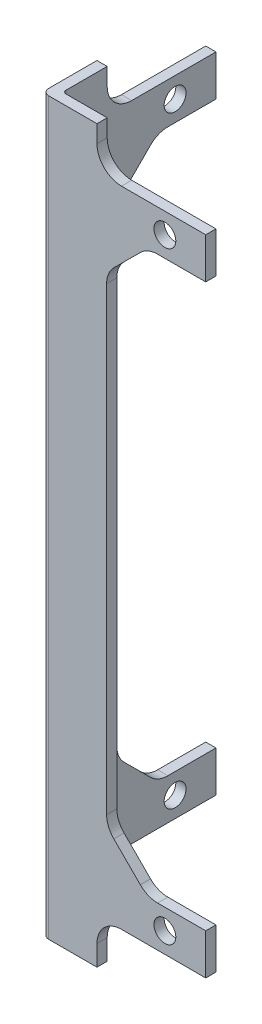
SolidWorks part; units mm, degrees
material "6061-T6 (SS)"
ref_plane "Front Plane" through (0, 0, 0) normal (0, 0, 1) x (1, 0, 0)
ref_plane "Top Plane" through (0, 0, 0) normal (0, 1, 0) x (1, 0, 0)
ref_plane "Right Plane" through (0, 0, 0) normal (1, 0, 0) x (0, 0, -1)
sketch "Sketch1" plane through (0, 0, 0) normal (0, 1, 0) x (1, 0, 0)
  line L1 (-12.7, -12.7) -> (12.7, -12.7)
  line L2 (-12.7, -12.7) -> (-12.7, 12.7)
  line L3 (-12.7, 12.7) -> (12.7, 12.7)
  line L4 (12.7, -12.7) -> (12.7, 12.7)
  line L5 (-12.7, -12.7) -> (12.7, 12.7) construction
  line L6 (-12.7, 12.7) -> (12.7, -12.7) construction
  point P0 (0, 0)
  dimension "D1" = 25.4
  dimension "D2" = 25.4
extrude "Boss-Extrude1" add sketch "Sketch1" along normal mid plane 113.5
sketch "Sketch2" plane through (0, 56.75, 0) normal (0, 1, 0) x (1, 0, 0)
  line L0 (-12.7, 12.7) -> (-12.7, -12.7) construction
  line L1 (12.7, 12.7) -> (-11.1125, 12.7)
  line L2 (12.7, 12.7) -> (12.7, -11.1125)
  line L3 (12.7, -11.1125) -> (-11.1125, -11.1125)
  line L4 (-11.1125, 12.7) -> (-11.1125, -11.1125)
  line L5 (-12.7, -12.7) -> (12.7, -12.7) construction
  dimension "D1" = 1.5875
  dimension "D2" = 1.5875
extrude "Cut-Extrude1" cut sketch "Sketch2" against normal through all
fillet "Fillet1" radius 0.508 1 edges at (-11.1125, 0, 11.1125)
hole_wizard "M3 Clearance Hole1" positions "Sketch3" profile "Sketch4" hole size "M3" standard "ANSI Metric" end condition through all
sketch "Sketch3" plane through (0, 0, 12.7) normal (0, 0, 1) x (1, 0, 0)
  line L1 (-12.7, 56.75) -> (12.7, 56.75) construction
  line L2 (12.7, 56.75) -> (12.7, -56.75) construction
  point P0 (6.35, 47.075)
  dimension "D1" = 6.35
  dimension "D2" = 9.675
sketch "Sketch4" plane through (6.35, 47.075, 12.7) normal (1, 0, 0) x (0, -1, 0)
  line L0 (0, 0) -> (0, 25.4)
  line L1 (0, 25.4) -> (1.7, 25.4)
  line L2 (1.7, 25.4) -> (1.7, 0)
  line L5 (1.7, 0) -> (0, 0)
  line L11 (0, -6.35) -> (0, 107.95) construction
  dimension "Thru Hole Dia." = 3.4
  dimension "Thru Hole Depth" = 25.4
hole_wizard "M3 Clearance Hole2" positions "Sketch5" profile "Sketch6" hole size "M3" standard "ANSI Metric" end condition through all
sketch "Sketch5" plane through (-12.7, 0, 0) normal (-1, 0, 0) x (0, 0, 1)
  line L1 (-12.7, 56.75) -> (12.7, 56.75) construction
  line L2 (-12.7, 56.75) -> (-12.7, -56.75) construction
  point P0 (-6.35, 47.075)
  dimension "D1" = 6.35
  dimension "D2" = 9.675
sketch "Sketch6" plane through (-12.7, 47.075, -6.35) normal (0, 1, 0) x (0, 0, 1)
  line L0 (0, 0) -> (0, 25.4)
  line L1 (0, 25.4) -> (1.7, 25.4)
  line L2 (1.7, 25.4) -> (1.7, 0)
  line L5 (1.7, 0) -> (0, 0)
  line L11 (0, -6.35) -> (0, 107.95) construction
  dimension "Thru Hole Dia." = 3.4
  dimension "Thru Hole Depth" = 25.4
hole_wizard "M3 Clearance Hole3" positions "Sketch7" profile "Sketch8" hole size "M3" standard "ANSI Metric" end condition through all
sketch "Sketch7" plane through (0, 0, 12.7) normal (0, 0, 1) x (1, 0, 0)
  line L2 (-12.7, -56.75) -> (12.7, -56.75) construction
  line L3 (12.7, 56.75) -> (12.7, -56.75) construction
  point P0 (6.35, -46.575)
  dimension "D1" = 6.35
  dimension "D2" = 10.175
sketch "Sketch8" plane through (6.35, -46.575, 12.7) normal (1, 0, 0) x (0, -1, 0)
  line L0 (0, 0) -> (0, 25.4)
  line L1 (0, 25.4) -> (1.7, 25.4)
  line L2 (1.7, 25.4) -> (1.7, 0)
  line L5 (1.7, 0) -> (0, 0)
  line L11 (0, -6.35) -> (0, 107.95) construction
  dimension "Thru Hole Dia." = 3.4
  dimension "Thru Hole Depth" = 25.4
hole_wizard "M3 Clearance Hole4" positions "Sketch9" profile "Sketch10" hole size "M3" standard "ANSI Metric" end condition through all
sketch "Sketch9" plane through (-12.7, 0, 0) normal (-1, 0, 0) x (0, 0, 1)
  line L1 (-12.7, -56.75) -> (12.7, -56.75) construction
  line L2 (-12.7, 56.75) -> (-12.7, -56.75) construction
  point P0 (-6.35, -46.575)
  dimension "D1" = 6.35
  dimension "D2" = 10.175
sketch "Sketch10" plane through (-12.7, -46.575, -6.35) normal (0, 1, 0) x (0, 0, 1)
  line L0 (0, 0) -> (0, 25.4)
  line L1 (0, 25.4) -> (1.7, 25.4)
  line L2 (1.7, 25.4) -> (1.7, 0)
  line L5 (1.7, 0) -> (0, 0)
  line L11 (0, -6.35) -> (0, 107.95) construction
  dimension "Thru Hole Dia." = 3.4
  dimension "Thru Hole Depth" = 25.4
fillet "Fillet2" radius 1 1 edges at (-12.7, 0, 12.7)
sketch "Sketch11" plane through (-12.7, 0, 0) normal (-1, 0, 0) x (0, 0, 1)
  line L0 (12.7, 56.75) -> (12.7, -56.75) construction
  line L1 (-12.7, 56.75) -> (4.2, 56.75)
  line L2 (-12.7, 56.75) -> (-12.7, 50.25)
  line L3 (-12.7, 50.25) -> (4.2, 50.25)
  line L4 (4.2, 56.75) -> (4.2, 50.25)
  line L6 (-12.7, -56.75) -> (4.2, -56.75)
  line L7 (-12.7, -56.75) -> (-12.7, -49.75)
  line L8 (-12.7, -49.75) -> (4.2, -49.75)
  line L9 (4.2, -56.75) -> (4.2, -49.75)
  dimension "D1" = 8.5
  dimension "D2" = 6.5
  dimension "D3" = 7
extrude "Cut-Extrude2" cut sketch "Sketch11" against normal up to next
sketch "Sketch12" plane through (0, 0, 12.7) normal (0, 0, 1) x (1, 0, 0)
  line L0 (-12.7, -56.75) -> (-12.7, 56.75) construction
  line L1 (12.7, 56.75) -> (-4.2, 56.75)
  line L2 (12.7, 56.75) -> (12.7, 50.25)
  line L3 (12.7, 50.25) -> (-4.2, 50.25)
  line L4 (-4.2, 56.75) -> (-4.2, 50.25)
  line L5 (12.7, -56.75) -> (-4.2, -56.75)
  line L6 (12.7, -56.75) -> (12.7, -49.75)
  line L7 (12.7, -49.75) -> (-4.2, -49.75)
  line L8 (-4.2, -56.75) -> (-4.2, -49.75)
  dimension "D1" = 8.5
  dimension "D2" = 7
  dimension "D3" = 8.5
  dimension "D4" = 6.5
extrude "Cut-Extrude3" cut sketch "Sketch12" against normal up to next
fillet "Fillet3" radius 3.81 4 edges at (-4.2, -49.75, 11.9062) (-11.9063, -49.75, 4.2) (-11.9063, 50.25, 4.2) (-4.2, 50.25, 11.9062)
sketch "Sketch13" plane through (-12.7, 0, 0) normal (-1, 0, 0) x (0, 0, 1)
  line L0 (4.2, -56.75) -> (4.2, 56.75) construction
  line L9 (2.7, -56.75) -> (2.7, 56.75) construction
  line L10 (-12.7, 50.25) -> (-12.7, -49.75) construction
  line L11 (2.7, -43.4) -> (-12.7, -43.4)
  line L12 (2.7, -43.4) -> (2.7, 43.9)
  line L13 (2.7, 43.9) -> (-12.7, 43.9)
  line L14 (-12.7, -43.4) -> (-12.7, 43.9)
  circle A2 centre (-6.35, 47.075) radius 1.7 construction
  circle A3 centre (-6.35, -46.575) radius 1.7 construction
  dimension "D2" = 3.175
  dimension "D3" = 3.175
  dimension "D1" = 1.5
extrude "Cut-Extrude4" cut sketch "Sketch13" against normal up to next
sketch "Sketch14" plane through (0, 0, 12.7) normal (0, 0, 1) x (1, 0, 0)
  line L0 (-4.2, 56.75) -> (-4.2, -56.75) construction
  line L1 (-2.7, 56.75) -> (-2.7, -56.75) construction
  line L2 (12.7, 50.25) -> (12.7, -49.75) construction
  line L3 (-2.7, -43.4) -> (12.7, -43.4)
  line L4 (-2.7, -43.4) -> (-2.7, 43.9)
  line L5 (-2.7, 43.9) -> (12.7, 43.9)
  line L6 (12.7, -43.4) -> (12.7, 43.9)
  circle A0 centre (6.35, 47.075) radius 1.7 construction
  circle A1 centre (6.35, -46.575) radius 1.7 construction
  dimension "D2" = 3.175
  dimension "D3" = 3.175
  dimension "D1" = 1.5
extrude "Cut-Extrude5" cut sketch "Sketch14" against normal up to next
chamfer "Chamfer2" distance 6.35 angle 45 4 edges at (-11.9063, 43.9, 2.7) (-2.7, 43.9, 11.9062) (-2.7, -43.4, 11.9062) (-11.9062, -43.4, 2.7)
fillet "Fillet5" radius 3.81 8 edges at (3.65, -43.4, 11.9062) (-2.7, -37.05, 11.9062) (-11.9063, -43.4, -3.65) (-11.9063, -37.05, 2.7) (-11.9063, 43.9, -3.65) (-11.9063, 37.55, 2.7) (-2.7, 37.55, 11.9062) (3.65, 43.9, 11.9062)
